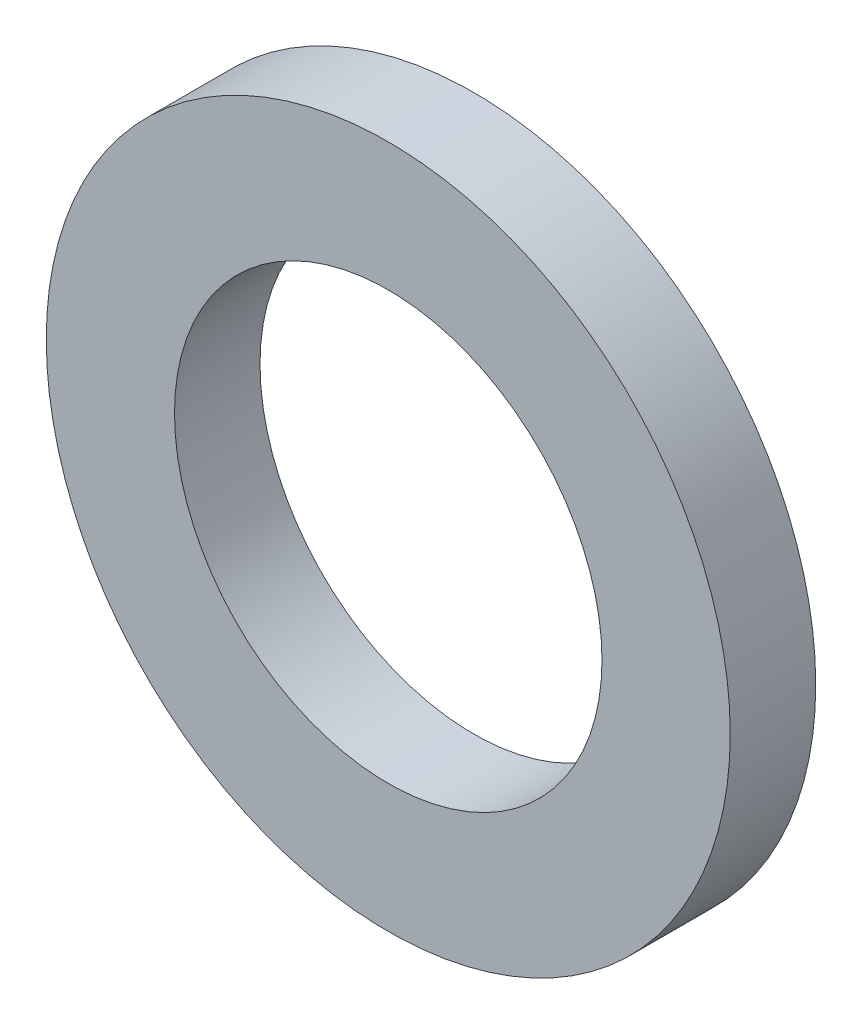
SolidWorks part; units mm, degrees
material "Leaded Commercial Bronze"
ref_plane "Front Plane" through (0, 0, 0) normal (0, 0, 1) x (1, 0, 0)
ref_plane "Top Plane" through (0, 0, 0) normal (0, 1, 0) x (1, 0, 0)
ref_plane "Right Plane" through (0, 0, 0) normal (1, 0, 0) x (0, 0, -1)
sketch "Sketch1" plane through (0, 0, 0) normal (0, 0, 1) x (1, 0, 0)
  circle A0 centre (0, 0) radius 12.7
  circle A1 centre (0, 0) radius 7.9375
  dimension "D1" = 25.4
  dimension "D2" = 15.875
extrude "Boss-Extrude1" add sketch "Sketch1" along normal blind 3.175
